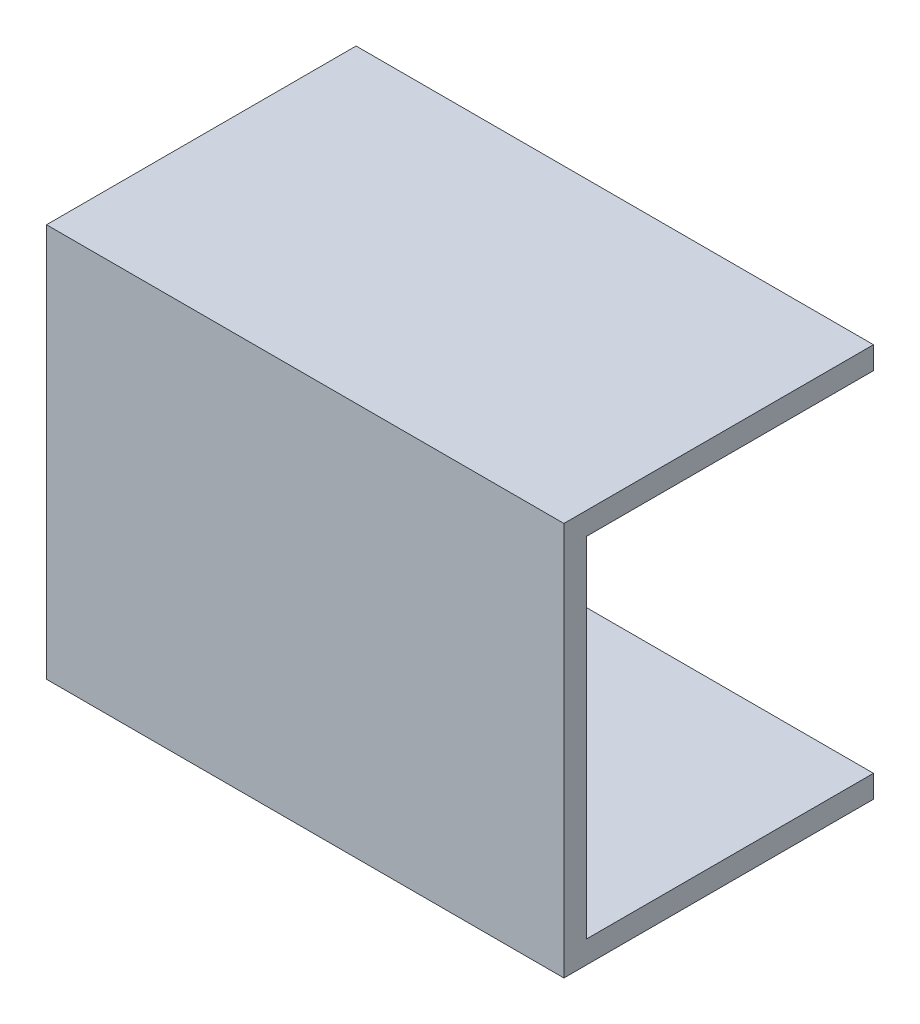
SolidWorks part; units mm, degrees
ref_plane "Front Plane" through (0, 0, 0) normal (0, 0, 1) x (1, 0, 0)
ref_plane "Top Plane" through (0, 0, 0) normal (0, 1, 0) x (1, 0, 0)
ref_plane "Right Plane" through (0, 0, 0) normal (1, 0, 0) x (0, 0, -1)
sketch "Sketch3" plane through (268.297, 0, 0) normal (-1, 0, 0) x (0, 0, 1)
  line L0 (3, -16.39) -> (28.5248, -16.39)
  line L1 (28.5248, -16.39) -> (28.5248, -47.39)
  line L2 (28.5248, -47.39) -> (3, -47.39)
extrude "Extrude-Thin1" add sketch "Sketch3" along normal blind 46 thin thin type one direction reverse wall 2
